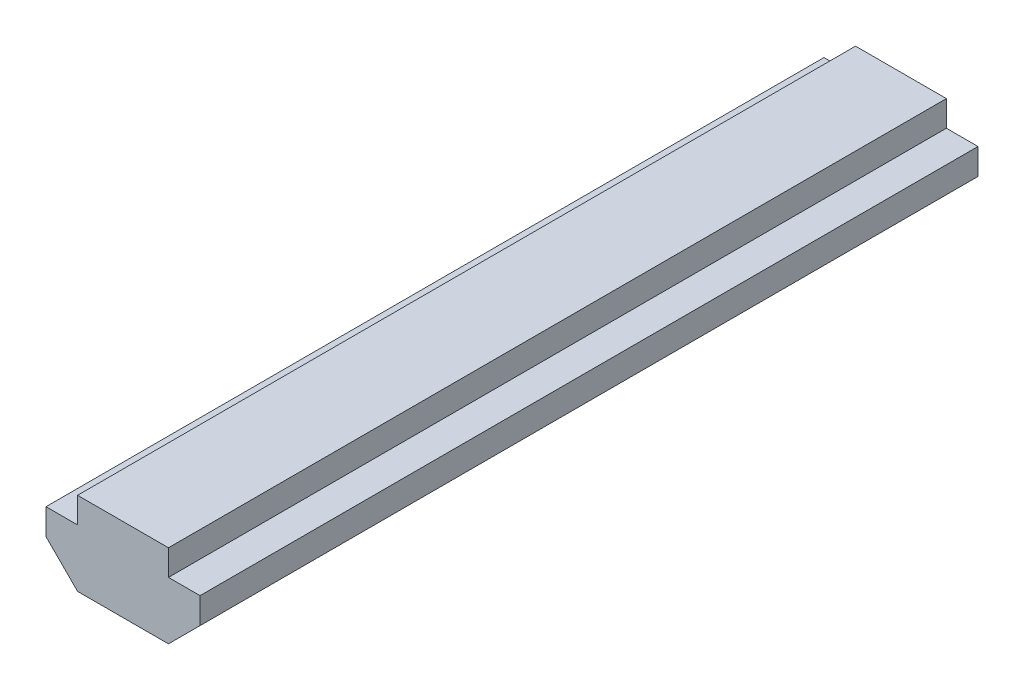
SolidWorks part; units mm, degrees
ref_plane "前视基准面" through (0, 0, 0) normal (0, 0, 1) x (1, 0, 0)
ref_plane "上视基准面" through (0, 0, 0) normal (0, 1, 0) x (1, 0, 0)
ref_plane "右视基准面" through (0, 0, 0) normal (1, 0, 0) x (0, 0, -1)
sketch "草图1" plane through (0, 0, 0) normal (0, 0, 1) x (1, 0, 0)
  line B0 (4.06, -7.4) -> (15.74, -7.4)
  line B1 (4.06, 3.3) -> (15.74, 3.3)
  line B2 (0, 0) -> (4.06, 0)
  line B3 (15.74, 0) -> (19.8, 0)
  line B4 (15.74, -7.4) -> (19.8, -3.34)
  line B5 (4.06, -7.4) -> (0, -3.34)
  line B6 (4.06, 0) -> (4.06, 3.3)
  line B7 (15.74, 0) -> (15.74, 3.3)
  line B8 (0, -3.34) -> (0, 0)
  line B9 (19.8, -3.34) -> (19.8, 0)
sketch_block_instance "A$C058B56FB-1"
sketch_block "A$C058B56FB"
extrude "凸台-拉伸1" add sketch "草图1" along normal blind 100
